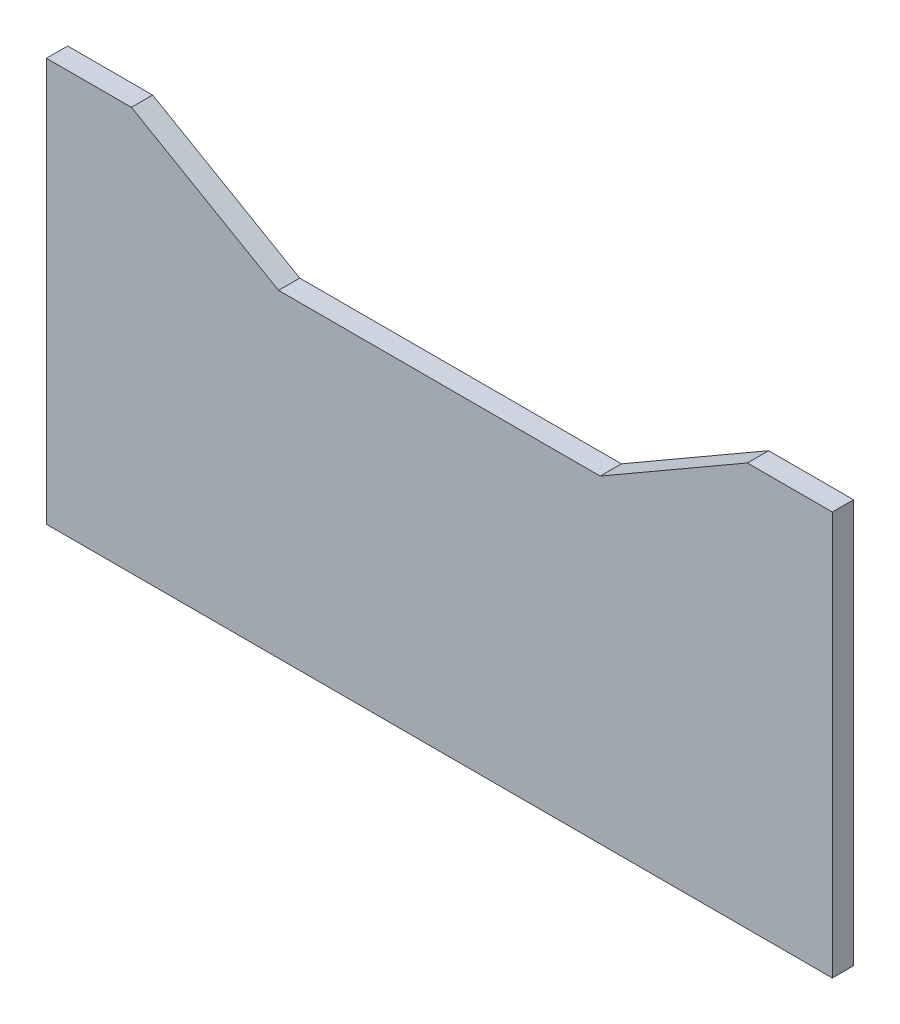
SolidWorks part; units mm, degrees
ref_plane "Plan de face" through (0, 0, 0) normal (0, 0, 1) x (1, 0, 0)
ref_plane "Plan de dessus" through (0, 0, 0) normal (0, 1, 0) x (1, 0, 0)
ref_plane "Plan de droite" through (0, 0, 0) normal (1, 0, 0) x (0, 0, -1)
sketch "Esquisse1" plane through (0, 0, 0) normal (0, 0, 1) x (1, 0, 0)
  line L0 (185, 190) -> (185, 150) construction
  line L1 (0, 0) -> (370, 0)
  line L2 (0, 0) -> (0, 190)
  line L3 (0, 190) -> (370, 190) construction
  line L4 (370, 0) -> (370, 190)
  line L5 (260.718, 150) -> (109.282, 150)
  line L6 (40, 190) -> (109.282, 150)
  line L7 (40, 190) -> (0, 190)
  line L8 (40, 190) -> (40, 150) construction
  line L9 (109.282, 150) -> (40, 150) construction
  line L10 (330, 190) -> (370, 190)
  line L11 (330, 190) -> (260.718, 150)
  dimension "D1" = 190
  dimension "D2" = 370
  dimension "D3" = 40
  dimension "D4" = 30
  dimension "D5" = 40
extrude "Boss.-Extru.1" add sketch "Esquisse1" along normal blind 10
